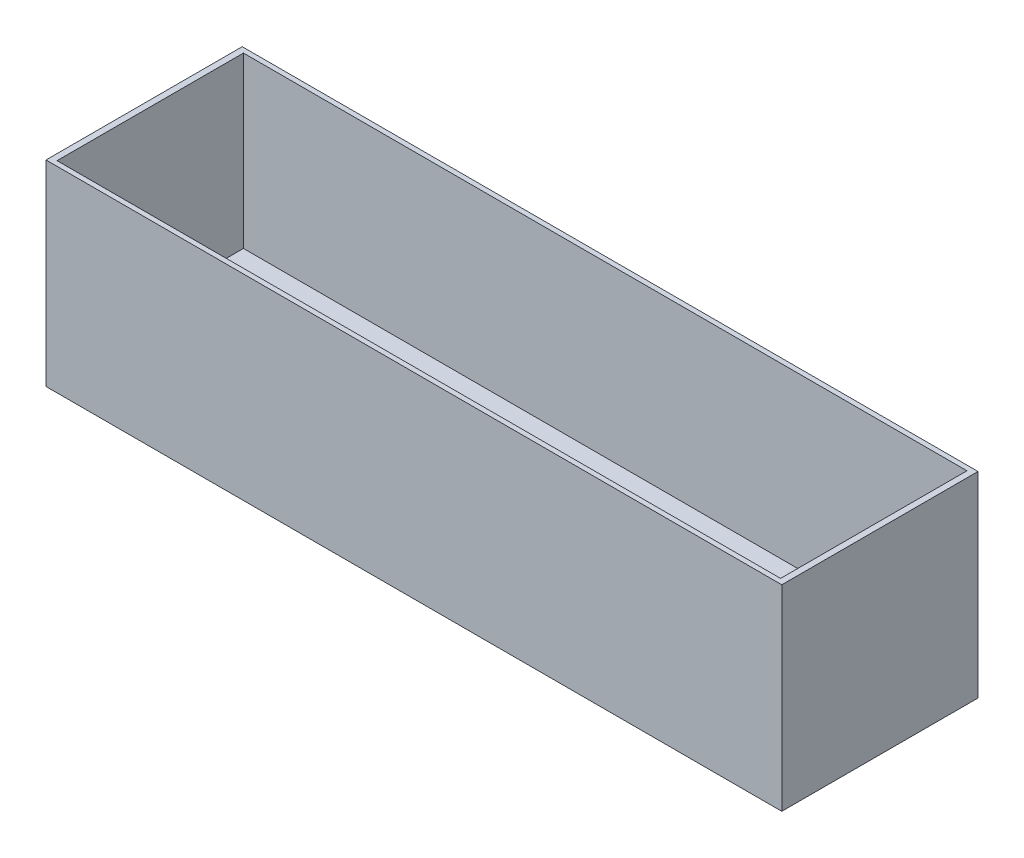
SolidWorks part; units mm, degrees
ref_plane "Front Plane" through (0, 0, 0) normal (0, 0, 1) x (1, 0, 0)
ref_plane "Top Plane" through (0, 0, 0) normal (0, 1, 0) x (1, 0, 0)
ref_plane "Right Plane" through (0, 0, 0) normal (1, 0, 0) x (0, 0, -1)
sketch "Sketch1" plane through (0, 0, 0) normal (0, 1, 0) x (1, 0, 0)
  line L1 (-1500, -400) -> (1500, -400)
  line L2 (-1500, -400) -> (-1500, 400)
  line L3 (-1500, 400) -> (1500, 400)
  line L4 (1500, -400) -> (1500, 400)
  line L5 (-1500, -400) -> (1500, 400) construction
  line L6 (-1500, 400) -> (1500, -400) construction
  point P0 (0, 0)
  dimension "D1" = 3000
  dimension "D2" = 800
extrude "Boss-Extrude2" add sketch "Sketch1" along normal blind 800 contours L2 L3 L4 L1
sketch "Sketch2" plane through (0, 800, 0) normal (0, 1, 0) x (1, 0, 0)
  line L1 (1475, 380) -> (-1475, 380)
  line L2 (1475, 380) -> (1475, -380)
  line L3 (1475, -380) -> (-1475, -380)
  line L4 (-1475, 380) -> (-1475, -380)
  line L5 (1475, 380) -> (-1475, -380) construction
  line L6 (1475, -380) -> (-1475, 380) construction
  point P0 (0, 0)
  dimension "D1" = 760
  dimension "D2" = 2950
extrude "Cut-Extrude1" cut sketch "Sketch2" against normal blind 690
